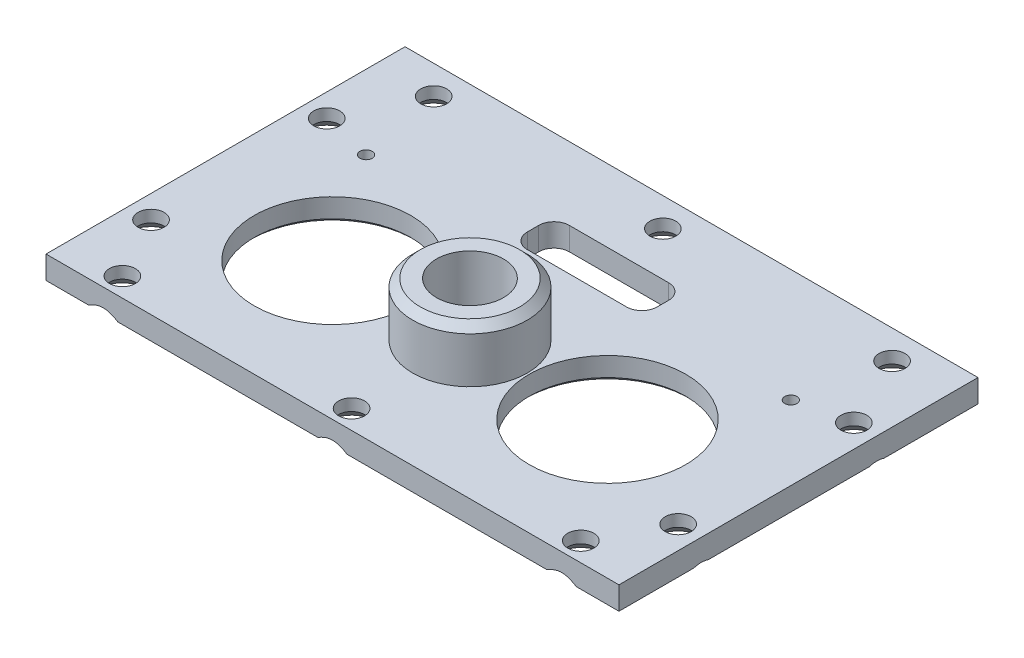
SolidWorks part; units mm, degrees
material "POM Ацеталь кополимер"
ref_plane "Спереди" through (0, 0, 0) normal (0, 0, 1) x (1, 0, 0)
ref_plane "Сверху" through (0, 0, 0) normal (0, 1, 0) x (1, 0, 0)
ref_plane "Справа" through (0, 0, 0) normal (1, 0, 0) x (0, 0, -1)
sketch "Эскиз1" plane through (0, 0, 0) normal (0, 1, 0) x (1, 0, 0)
  line L0 (-18, -29) -> (0, -29) construction
  line L1 (-37.5, 0) -> (37.5, 0)
  line L2 (-37.5, 0) -> (-37.5, -47)
  line L3 (-37.5, -47) -> (37.5, -47)
  line L4 (37.5, 0) -> (37.5, -47)
  line L7 (0, -29) -> (18, -29) construction
  circle A3 centre (18, -29) radius 10.25
  circle A6 centre (-18, -29) radius 10.25
  circle A7 centre (0, -29) radius 4.39
  point P13 (0, 0)
  dimension "D3" = 20.5
  dimension "D6" = 8.78
  dimension "D4" = 36
  dimension "D1" = 75
  dimension "D2" = 47
  dimension "D5" = 29
extrude "База" add sketch "Эскиз1" along normal blind 3
hole_wizard "Крепление стенок M3" positions "Эскиз4" profile "Эскиз3" countersink size "M3" standard "ISO" end condition through all
sketch "Эскиз4" plane through (0, 0, 0) normal (0, -1, 0) x (-1, 0, 0)
  line L0 (0, -44.5) -> (0, -47) construction
  line L1 (37.5, -47) -> (-37.5, -47) construction
  line L8 (30, -44.5) -> (0, -44.5) construction
  line L9 (0, -44.5) -> (-30, -44.5) construction
  line L10 (34.5, -36.25) -> (34.5, -24.75) construction
  line L11 (34.5, -24.75) -> (34.5, -13.25) construction
  line L18 (34.5, -13.25) -> (37.5, -13.25) construction
  line L19 (37.5, 0) -> (37.5, -47) construction
  line L22 (-34.5, -13.25) -> (-37.5, -13.25) construction
  line L23 (-37.5, -47) -> (-37.5, 0) construction
  line L24 (-37.5, 0) -> (37.5, 0) construction
  point P0 (0, -44.5)
  point P2 (-30, -44.5)
  point P4 (30, -44.5)
  point P6 (0, -3.75)
  point P8 (30, -3.75)
  point P10 (-30, -3.75)
  point P34 (34.5, -36.25)
  point P36 (-34.5, -36.25)
  point P38 (-34.5, -13.25)
  point P40 (34.5, -13.25)
  dimension "D1" = 2.5
  dimension "D2" = 60
  dimension "D3" = 23
  dimension "D4" = 3
  dimension "D5" = 3.75
  dimension "D6" = 24.75
sketch "Эскиз3" plane through (0, 0, 44.5) normal (1, 0, 0) x (0, 0, -1)
  line L0 (0, 0) -> (0, 3)
  line L1 (0, 3) -> (1.7, 3)
  line L2 (1.7, 3) -> (1.7, 1.45)
  line L3 (1.7, 1.45) -> (3.15, 0)
  line L5 (3.15, 0) -> (0, 0)
  line L6 (-1.7, 1.45) -> (-3.15, 0) construction
  line L11 (0, -6.35) -> (0, 107.95) construction
  dimension "Диаметр сквозного отверстия" = 3.4
  dimension "Глубина сквозного отверстия" = 3
  dimension "Диаметр передней зенковки" = 6.3
  dimension "Угол передней зенковки" = 90
chamfer "Фаска1" distance 0.5 angle 45 3 edges at (18, 0, 39.25) (0, 0, 33.39) (-18, 0, 39.25)
sketch "Эскиз6" plane through (0, 0, 0) normal (0, -1, 0) x (1, 0, 0)
  line L0 (37.5, 0) -> (-37.5, 0) construction
  line L1 (-8.5, 9.5) -> (8.5, 9.5)
  line L2 (-8.5, 9.5) -> (-8.5, 15)
  line L3 (-8.5, 15) -> (8.5, 15)
  line L4 (8.5, 9.5) -> (8.5, 15)
  point P5 (0, 9.5)
  point P6 (0, 15)
  dimension "D1" = 9.5
  dimension "D2" = 17
  dimension "D3" = 5.5
extrude "Вырез-Вытянуть1" cut sketch "Эскиз6" against normal through all
fillet "Скругление1" radius 2 4 edges at (8.5, 1.5, 9.5) (8.5, 1.5, 15) (-8.5, 1.5, 15) (-8.5, 1.5, 9.5)
hole_wizard "Отверстие обработанное метчиком M21" positions "Эскиз9" profile "Эскиз8" tap size "M2" standard "DIN" end condition through all
sketch "Эскиз9" plane through (0, 0, 0) normal (0, -1, 0) x (-1, 0, 0)
  point P0 (27.8, -14.8)
  point P3 (-27.8, -14.8)
sketch "Эскиз8" plane through (-27.8, 0, 14.8) normal (1, 0, 0) x (0, 0, -1)
  line L0 (0, 0) -> (0, 3)
  line L1 (0, 3) -> (0.8, 3)
  line L2 (0.8, 3) -> (0.8, 0)
  line L5 (0.8, 0) -> (0, 0)
  line L11 (0, -6.35) -> (0, 107.95) construction
  dimension "Диаметр проходного сверла" = 1.6
  dimension "Глубина проходного сверла" = 3
cosmetic thread "Отверстие резьбы1" parameters "D2"=2
cosmetic thread "Отверстие резьбы2" parameters "D2"=2
sketch "Эскиз10" plane through (0, 3, 0) normal (0, 1, 0) x (1, 0, 0)
  circle A0 centre (0, -29) radius 4.39
  circle A1 centre (0, -29) radius 7.5
  circle A2 centre (0, -29) radius 4.39 construction
  dimension "D1" = 15
extrude "Бобышка-Вытянуть1" add sketch "Эскиз10" along normal blind 7
chamfer "Фаска2" distance 1 angle 45 1 edges at (0, 10, 36.5)
